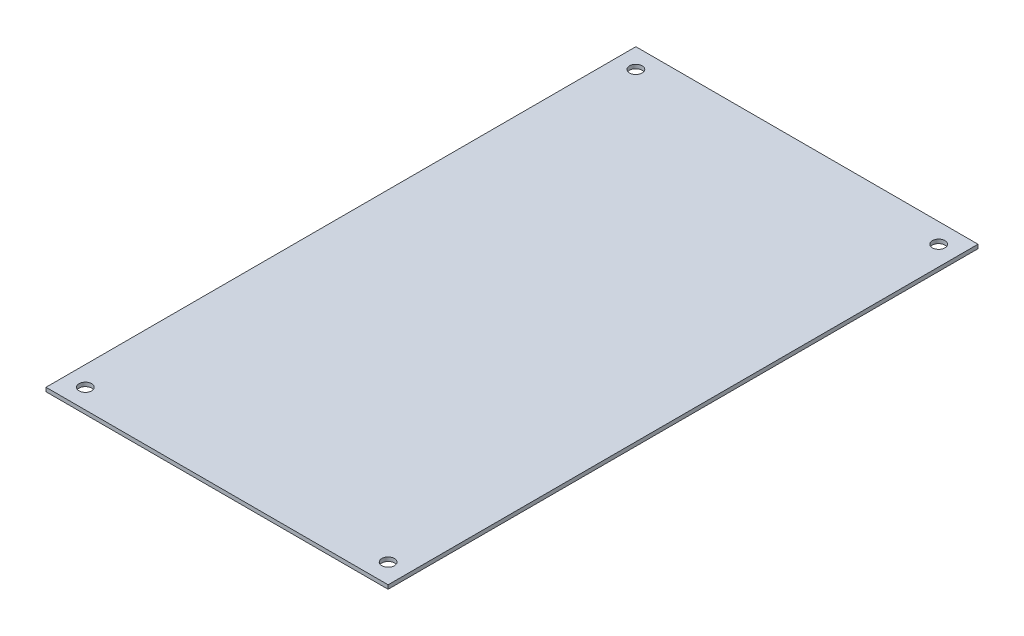
SolidWorks part; units mm, degrees
material "ABS"
ref_plane "Front Plane" through (0, 0, 0) normal (0, 0, 1) x (1, 0, 0)
ref_plane "Top Plane" through (0, 0, 0) normal (0, 1, 0) x (1, 0, 0)
ref_plane "Right Plane" through (0, 0, 0) normal (1, 0, 0) x (0, 0, -1)
sketch "Sketch1" plane through (0, 0, 0) normal (0, 1, 0) x (1, 0, 0)
  line L0 (-43.5, -75) -> (-43.5, 75)
  line L1 (-38.5, -70) -> (38.5, -70)
  line L2 (-38.5, -70) -> (-38.5, 70)
  line L3 (-38.5, 70) -> (38.5, 70)
  line L4 (38.5, -70) -> (38.5, 70)
  line L5 (-38.5, -70) -> (38.5, 70) construction
  line L6 (-38.5, 70) -> (38.5, -70) construction
  line L7 (-43.5, 75) -> (43.5, 75)
  line L8 (43.5, -75) -> (43.5, 75)
  line L9 (-43.5, -75) -> (43.5, -75)
  circle A0 centre (-38.5, 70) radius 1.6
  circle A1 centre (38.5, 70) radius 1.6
  circle A2 centre (38.5, -70) radius 1.6
  circle A3 centre (-38.5, -70) radius 1.6
  point P0 (0, 0)
  dimension "D4" = 3.2
  dimension "D1" = 77
  dimension "D2" = 140
  dimension "D3" = 5
  dimension "D5" = 2
  dimension "D6" = 2
extrude "Boss-Extrude1" add sketch "Sketch1" along normal blind 1 contours A3 L1 A2 L4 A1 L3 A0 L2 | L0 L9 L8 L7 A3 L2 A0 L3 A1 L4 A2 L1
